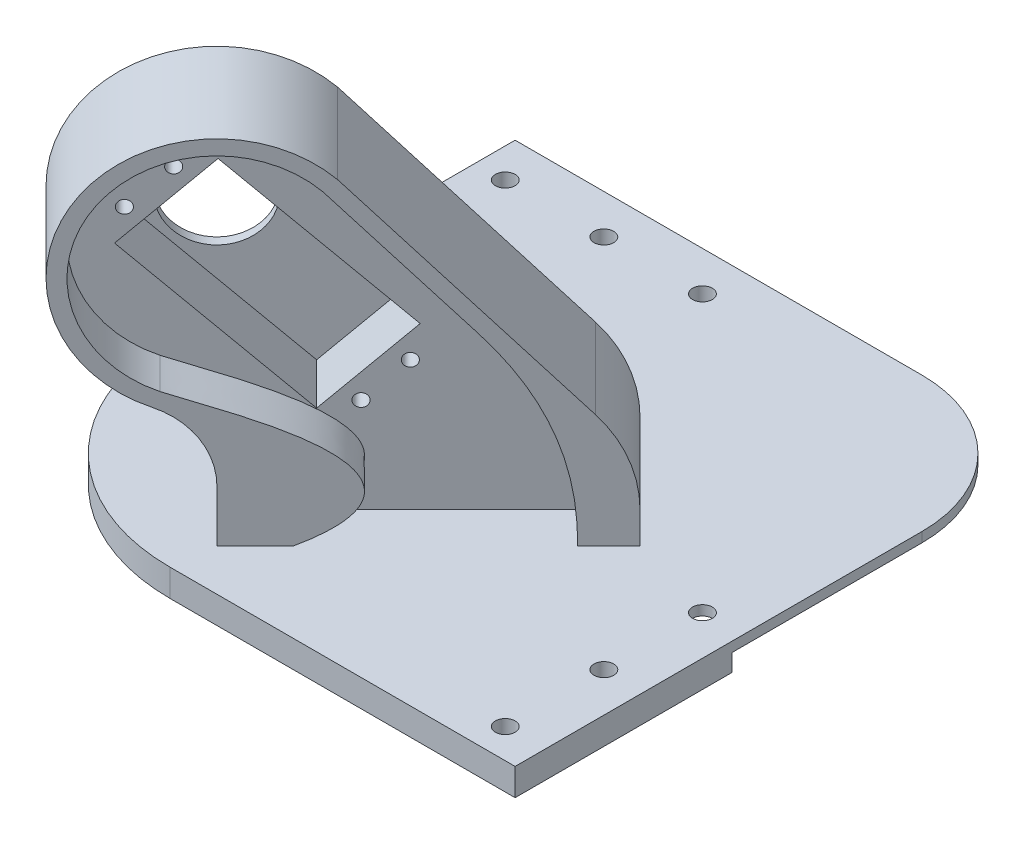
SolidWorks part; units mm, degrees
ref_plane "Front Plane" through (0, 0, 0) normal (0, 0, 1) x (1, 0, 0)
ref_plane "Top Plane" through (0, 0, 0) normal (0, 1, 0) x (1, 0, 0)
ref_plane "Right Plane" through (0, 0, 0) normal (1, 0, 0) x (0, 0, -1)
sketch "Sketch2" plane through (0, 0, 0) normal (0, 1, 0) x (1, 0, 0)
  line L0 (-63.65, -46.35) -> (46.35, -46.35)
  line L1 (46.35, -46.35) -> (46.35, 63.65)
  line L2 (46.35, 63.65) -> (-63.65, 63.65)
  line L3 (-63.65, 63.65) -> (-63.65, -46.35)
  dimension "D1" = 110
  dimension "D2" = 110
extrude "Boss-Extrude1" add sketch "Sketch2" along normal blind 5.5
ref_plane "Plane1" through (-8.65, 0, -8.65) normal (-0.7071, 0, -0.7071) x (-0.7071, 0, 0.7071)
sketch "Sketch7" plane through (-8.65, 0, -8.65) normal (-0.7071, 0, -0.7071) x (-0.7071, 0, 0.7071)
  line L0 (39.7602, 15.9595) -> (39.7602, 5.5)
  line L6 (-10.597, 29.5362) -> (27.579, 67.7122)
  line L7 (-40.5488, 5.5) -> (39.7602, 5.5)
  line L11 (-17.9194, 11.8586) -> (-17.9194, 5.5)
  line L12 (-17.9194, 5.5) -> (39.7602, 5.5)
  line L13 (27.579, 67.7122) -> (-10.597, 29.5362)
  line L14 (39.7602, 15.9595) -> (39.7602, 5.5)
  line L15 (0, 5.5) -> (77.7817, 5.5) construction
  arc A4 (50.9346, 32.6152) -> (27.579, 67.7122) centre (42.7817, 52.5094) ccw
  arc A5 (50.9346, 32.6152) -> (39.7602, 15.9595) centre (57.7602, 15.9595) ccw
  arc A6 (-10.597, 29.5362) -> (-17.9194, 11.8586) centre (7.0806, 11.8586) ccw
  point P5 (0, 0)
  point P6 (0, 0)
  point P10 (0, 0)
  point P12 (0, 0)
  point P13 (0, 0)
  point P14 (0, 0)
  point P17 (0, 0)
  point P21 (0, 0)
  point P22 (0, 0)
  dimension "D1" = 25
  dimension "D4" = 43
  dimension "D2" = 35
  dimension "D3" = 18
  dimension "D5" = 45
extrude "Boss-Extrude2" add sketch "Sketch7" against normal blind 14
ref_plane "Plane2" through (-7.2358, 0, -7.2358) normal (-0.7071, 0, -0.7071) x (-0.7071, 0, 0.7071)
sketch "Sketch8" plane through (-7.2358, 0, -7.2358) normal (-0.7071, 0, -0.7071) x (-0.7071, 0, 0.7071)
  line L0 (-10.597, 29.5362) -> (27.579, 67.7122) construction
  line L1 (13.6136, 38.1905) -> (42.605, 67.1819)
  line L2 (13.6136, 38.1905) -> (28.4628, 23.3413)
  line L3 (28.4628, 23.3413) -> (57.4542, 52.3327)
  line L4 (42.605, 67.1819) -> (57.4542, 52.3327)
  line L5 (13.6136, 38.1905) -> (57.4542, 52.3327) construction
  line L6 (28.4628, 23.3413) -> (42.605, 67.1819) construction
  point P0 (35.5339, 45.2616)
  point P11 (42.7817, 52.5094)
  dimension "D1" = 41
  dimension "D2" = 21
  dimension "D3" = 90
  dimension "D4" = 20.5
  dimension "D5" = 90
  dimension "D6" = 10.25
  dimension "D7" = 10.5
extrude "Cut-Extrude5" cut sketch "Sketch8" against normal up to next
sketch "Sketch9" plane through (1.2495, 0, 1.2495) normal (0.7071, 0, 0.7071) x (0.7071, 0, -0.7071)
  line L0 (-42.605, 67.1819) -> (-57.4542, 52.3327) construction
  line L3 (-50.0296, 59.7573) -> (-30.8512, 40.5788) construction
  circle A0 centre (-48.9689, 65.7677) radius 1.3
  circle A1 centre (-56.04, 58.6966) radius 1.3
  circle A2 centre (-22.0989, 24.7555) radius 1.3
  circle A3 centre (-15.0278, 31.8266) radius 1.3
  dimension "D1" = 2.6
  dimension "D5" = 5
  dimension "D6" = 90
  dimension "D2" = 3.5
  dimension "D3" = 2
  dimension "D4" = 2
extrude "Cut-Extrude6" cut sketch "Sketch9" against normal blind 7.5
sketch "Sketch11" plane through (-8.65, 0, -8.65) normal (-0.7071, 0, -0.7071) x (-0.7071, 0, 0.7071)
  circle A0 centre (42.7817, 52.5094) radius 9
  dimension "D1" = 18
extrude "Cut-Extrude9" cut sketch "Sketch11" against normal up to next
sketch "Sketch17" plane through (1.2495, 0, 1.2495) normal (0.7071, 0, 0.7071) x (0.7071, 0, -0.7071)
  line L0 (12.7183, 31.6576) -> (-25.4576, 69.8335)
  line L1 (-42.7602, 15.9595) -> (-42.7602, 2.5)
  line L2 (-42.7602, 2.5) -> (20.9194, 2.5)
  line L3 (20.9194, 2.5) -> (20.9194, 11.8586)
  line L4 (10.597, 29.5362) -> (-27.579, 67.7122)
  line L5 (-39.7602, 15.9595) -> (-39.7602, 5.5)
  line L6 (-39.7602, 5.5) -> (17.9194, 5.5)
  line L7 (17.9194, 5.5) -> (17.9194, 11.8586)
  line L9 (-39.7602, 15.9595) -> (-39.7602, 5.5)
  line L10 (-39.7602, 5.5) -> (17.9194, 5.5)
  line L12 (-42.7602, 5.5) -> (20.9194, 5.5)
  line L14 (-25.4576, 69.8335) -> (11.539, 28.5412)
  line L15 (-27.579, 67.7122) -> (9.3058, 26.5379)
  line L16 (14.9194, 11.8586) -> (14.9194, 5.5)
  line L17 (17.9194, 5.5) -> (-39.7602, 5.5) construction
  line L18 (10.597, 29.5362) -> (-27.579, 67.7122) construction
  line L22 (17.9194, 5.5) -> (17.9194, 11.8586) construction
  line L23 (17.9194, 5.5) -> (17.9194, 11.8586)
  arc A0 (-25.4576, 69.8335) -> (-52.0722, 29.8392) centre (-42.7817, 52.5094) ccw
  arc A1 (-42.7602, 15.9595) -> (-52.0722, 29.8392) centre (-57.7602, 15.9595) ccw
  arc A2 (20.9194, 11.8586) -> (12.7183, 31.6576) centre (-7.0806, 11.8586) ccw
  arc A3 (-27.579, 67.7122) -> (-50.9346, 32.6152) centre (-42.7817, 52.5094) ccw
  arc A4 (-39.7602, 15.9595) -> (-50.9346, 32.6152) centre (-57.7602, 15.9595) ccw
  arc A5 (17.9194, 11.8586) -> (10.597, 29.5362) centre (-7.0806, 11.8586) ccw
  arc A6 (-27.579, 67.7122) -> (-50.9346, 32.6152) centre (-42.7817, 52.5094) ccw
  arc A7 (-39.7602, 15.9595) -> (-50.9346, 32.6152) centre (-57.7602, 15.9595) ccw
  arc A8 (17.9194, 11.8586) -> (10.597, 29.5362) centre (-7.0806, 11.8586) ccw
  arc A9 (14.9194, 11.8586) -> (8.4757, 27.4149) centre (-7.0806, 11.8586) ccw
  point P22 (0, 0)
  point P31 (0, 0)
  dimension "D1" = 0
  dimension "D2" = 3
  dimension "D3" = 3
extrude "Boss-Extrude7" add sketch "Sketch17" along normal blind 9 and the other way up to surface other way up to face at (-45.2652, 52.5094, 27.9652)
sketch "Sketch25" plane through (1.2495, 0, 1.2495) normal (0.7071, 0, 0.7071) x (0.7071, 0, -0.7071)
  line L0 (-39.7602, 15.9595) -> (-39.7602, 5.5)
  line L2 (-39.7602, 15.9595) -> (-39.7602, 5.5) construction
  line L3 (-27.579, 67.7122) -> (9.3058, 26.5379) construction
  line L4 (14.9194, 5.5) -> (-39.7602, 5.5) construction
  line L5 (14.9194, 11.8586) -> (14.9194, 5.5) construction
  line L6 (14.9194, 5.5) -> (-39.7602, 5.5)
  line L7 (14.9194, 11.8586) -> (14.9194, 5.5)
  line L8 (-27.579, 67.7122) -> (9.3058, 26.5379)
  line L9 (17.9194, 5.5) -> (-42.7602, 5.5) construction
  arc A0 (-39.7602, 15.9595) -> (-50.9346, 32.6152) centre (-57.7602, 15.9595) ccw construction
  arc A1 (-27.579, 67.7122) -> (-50.9346, 32.6152) centre (-42.7817, 52.5094) ccw construction
  arc A2 (-39.7602, 15.9595) -> (-50.9346, 32.6152) centre (-57.7602, 15.9595) ccw
  arc A3 (14.9194, 11.8586) -> (9.3058, 26.5379) centre (-7.0806, 11.8586) ccw construction
  arc A4 (14.9194, 11.8586) -> (9.3058, 26.5379) centre (-7.0806, 11.8586) ccw
  spline S0 degree 3 poles (-50.9346, 32.6152) (-42.2861, 29.0709) (-3.4989, 18.5304) (-31.7602, 5.5) knots 0 0 0 0 1 1 1 1
  spline S1 degree 2 poles (-5.2791, 42.819) (9.4043, 26.428) (8.9194, 5.5) knots 0 0 0 1 1 1
  dimension "D2" = 8
  dimension "D1" = 6
extrude "Boss-Extrude10" add sketch "Sketch25" along normal up to surface (9 mm away) contours S0 L6 L0 A2 | A4 S1 A2 S0 L8 up to face at (-6.1679, 26.246, 21.3948)
ref_plane "Plane3" through (-11.427, 0, 11.427) normal (-0.7071, 0, 0.7071) x (0.7071, 0, 0.7071)
sketch "Sketch26" plane through (0, 0, 0) normal (0, -1, 0) x (1, 0, 0)
  line L0 (-2.35, -23.65) -> (-2.35, -63.65)
  line L1 (-2.35, -63.65) -> (46.35, -63.65)
  line L2 (46.35, -63.65) -> (46.35, 2.35)
  line L3 (46.35, 2.35) -> (23.65, 2.35)
  arc A0 (23.65, 2.35) -> (-2.35, -23.65) centre (23.65, -23.65) ccw
  point P8 (0, 0)
  point P9 (-95.0745, -111.0372)
  point P10 (46.35, -46.35)
extrude "Cut-Extrude10" cut sketch "Sketch26" against normal blind 3.5
hole_wizard "Ø4.0 (4) Diameter Hole3" positions "Sketch33" profile "Sketch34" hole size "Ø4.0" standard "ANSI Metric" end condition through all
sketch "Sketch33" plane through (0, 5.5, 0) normal (0, 1, 0) x (1, 0, 0)
  line L0 (-63.65, -46.35) -> (46.35, -46.35) construction
  line L1 (46.35, -46.35) -> (46.35, 63.65) construction
  point P0 (38.35, -40.35)
  point P5 (38.35, -20.35)
  point P7 (38.35, -0.35)
  point P14 (46.35, -37.8252)
  dimension "D1" = 6
  dimension "D2" = 8
  dimension "D3" = 8
  dimension "D4" = 20
  dimension "D5" = 8
sketch "Sketch34" plane through (38.35, 5.5, 40.35) normal (1, 0, 0) x (0, 0, 1)
  line L0 (0, 0) -> (0, 5.5)
  line L1 (0, 5.5) -> (2, 5.5)
  line L2 (2, 5.5) -> (2, 0)
  line L5 (2, 0) -> (0, 0)
  line L11 (0, -6.35) -> (0, 107.95) construction
  dimension "Thru Hole Dia." = 4
  dimension "Thru Hole Depth" = 5.5
mirror "Mirror1" about plane through (-8.65, 0, -8.65) normal (-0.7071, 0, -0.7071) of "Ø4.0 (4) Diameter Hole3"
fillet "Fillet1" radius 27.5 1 edges at (46.35, 4.5, -63.65)
fillet "Fillet2" radius 40 1 edges at (-63.65, 2.75, 46.35)
